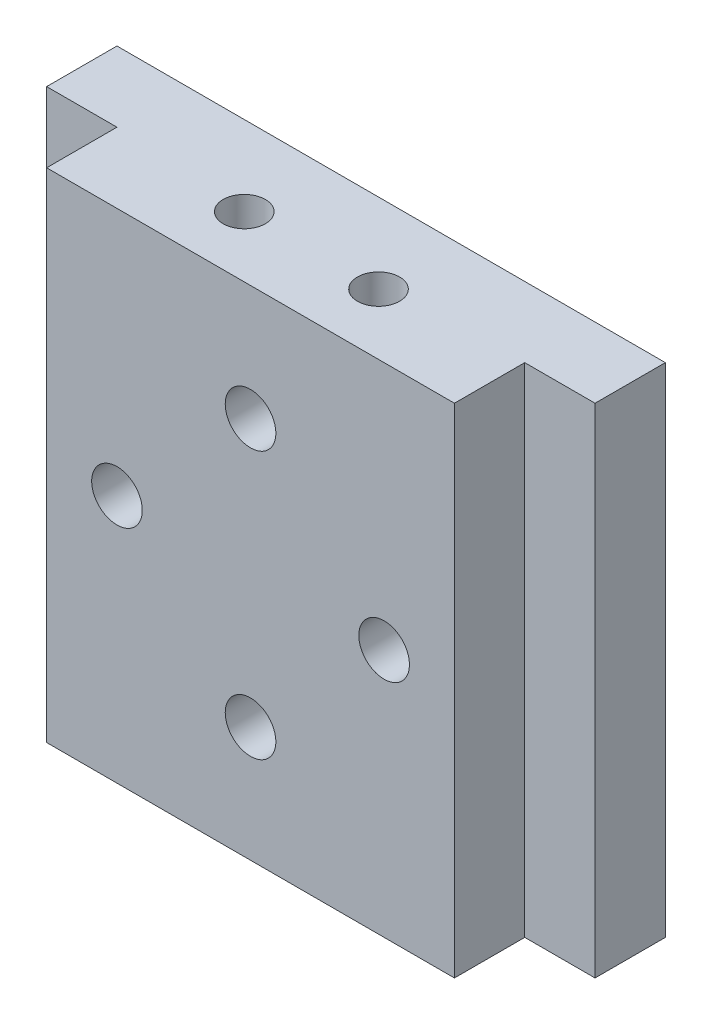
SolidWorks part; units mm, degrees
ref_plane "Front Plane" through (0, 0, 0) normal (0, 0, 1) x (1, 0, 0)
ref_plane "Top Plane" through (0, 0, 0) normal (0, 1, 0) x (1, 0, 0)
ref_plane "Right Plane" through (0, 0, 0) normal (1, 0, 0) x (0, 0, -1)
sketch "Sketch1" plane through (0, 0, 0) normal (0, 1, 0) x (1, 0, 0)
  line L0 (-14.5, 0) -> (14.5, 0)
  line L3 (19.5, 5) -> (19.5, 10)
  line L4 (19.5, 10) -> (-19.5, 10)
  line L5 (-19.5, 10) -> (-19.5, 5)
  line L8 (-19.5, 5) -> (-14.5, 5)
  line L9 (-14.5, 5) -> (-14.5, 0)
  line L10 (14.5, 0) -> (14.5, 5)
  line L11 (14.5, 5) -> (19.5, 5)
  point P3 (0, 0)
  dimension "D1" = 39
  dimension "D2" = 5
  dimension "D3" = 5
  dimension "D4" = 5
extrude "Boss-Extrude1" add sketch "Sketch1" along normal mid plane 35.4
sketch "Sketch2" plane through (0, 0, 0) normal (0, 0, 1) x (1, 0, 0)
  line L0 (0, -9.5) -> (0, 9.5) construction
  line L1 (-9.5, 0) -> (9.5, 0) construction
  point P4 (0, 0)
  point P8 (0, 0)
hole_wizard "CSK for M3 Flat Head Machine Screw1" positions "Sketch4" profile "Sketch5" countersink size "M3" standard "ANSI Metric" end condition up to next
sketch "Sketch4" plane through (0, 0, -10) normal (0, 0, -1) x (-1, 0, 0)
  point P0 (0, 9.5)
  point P3 (-9.5, 0)
  point P6 (9.5, 0)
  point P9 (0, -9.5)
sketch "Sketch5" plane through (0, 9.5, -10) normal (1, 0, 0) x (0, 1, 0)
  line L0 (0, 0) -> (0, 10)
  line L1 (0, 10) -> (1.8, 10)
  line L2 (1.8, 10) -> (1.8, 1.35)
  line L3 (1.8, 1.35) -> (3.15, 0)
  line L5 (3.15, 0) -> (0, 0)
  line L6 (-1.8, 1.35) -> (-3.15, 0) construction
  line L11 (0, -6.35) -> (0, 107.95) construction
  dimension "Thru Hole Dia." = 3.6
  dimension "Thru Hole Depth" = 10
  dimension "Near C'Sink Dia." = 6.3
  dimension "Near C'Sink Angle" = 90
sketch "Sketch8" plane through (0, 17.7, 0) normal (0, 1, 0) x (1, 0, 0)
  line L0 (-7.7, 5) -> (-1.8, 5) construction
  line L1 (-7.7, 0) -> (-7.7, 8.65) construction
  line L2 (-1.8, 8.65) -> (-1.8, 0) construction
  line L3 (1.8, 5) -> (7.7, 5) construction
  line L4 (1.8, 0) -> (1.8, 8.65) construction
  line L5 (7.7, 8.65) -> (7.7, 0) construction
  line L6 (-19.5, 5) -> (-14.5, 5) construction
  line L7 (-4.75, 5) -> (-4.75, 8.65) construction
  line L8 (-11.3, 8.65) -> (-7.7, 8.65) construction
  line L9 (4.75, 5) -> (4.75, 8.65) construction
  line L10 (-1.8, 8.65) -> (1.8, 8.65) construction
  line L11 (-3.25, 6.825) -> (-6.25, 6.825) construction
  line L12 (6.25, 6.825) -> (3.25, 6.825) construction
  point P25 (-4.75, 6.825)
  point P28 (4.75, 6.825)
  dimension "D1" = 3
sketch "Sketch9" plane through (0, 17.7, 0) normal (0, 1, 0) x (1, 0, 0)
  line L0 (-7.7, 0) -> (-1.8, 0) construction
  line L1 (-14.5, 0) -> (14.5, 0) construction
  line L2 (1.8, 0) -> (7.7, 0) construction
  line L3 (-4.75, 0) -> (-4.75, 8.65) construction
  line L4 (-7.7, 8.65) -> (-1.8, 8.65) construction
  line L5 (1.8, 8.65) -> (7.7, 8.65) construction
  line L6 (4.75, 8.65) -> (4.75, 0) construction
  line L7 (-5.25, 4.325) -> (-4.25, 4.325) construction
  line L8 (4.25, 4.325) -> (5.25, 4.325) construction
  point P24 (-4.75, 4.325)
  point P27 (4.75, 4.325)
  dimension "D1" = 1
hole_wizard "Ø3.0mm Press Dowel Hole1" positions "3DSketch1" profile "Sketch10" hole size "Ø3.0" standard "ANSI Metric" end condition up to next
sketch3d "3DSketch1"
  line L0 (-14.5, 17.7, 0) -> (-4.7739, 17.7, 0) construction
  line L1 (-14.5, 17.7, 0) -> (14.5, 17.7, 0) construction
  line L2 (-4.7739, 17.7, 0) -> (-4.7739, 17.7, -4.3276) construction
  line L8 (14.5, 17.7, 0) -> (4.7739, 17.7, 0) construction
  line L9 (4.7739, 17.7, 0) -> (4.7739, 17.7, -4.3276) construction
  point P0 (-4.7739, 17.7, -4.3276)
  point P2 (4.7739, 17.7, -4.3276)
  dimension "D1" = 9.7261
  dimension "D2" = 4.3276
sketch "Sketch10" plane through (-4.7739, 17.7, -4.3276) normal (1, 0, 0) x (0, 0, 1)
  line L0 (0, 0) -> (0, 35.4)
  line L1 (0, 35.4) -> (1.5, 35.4)
  line L2 (1.5, 35.4) -> (1.5, 0)
  line L5 (1.5, 0) -> (0, 0)
  line L11 (0, -6.35) -> (0, 107.95) construction
  dimension "Thru Hole Dia." = 3
  dimension "Thru Hole Depth" = 35.4
